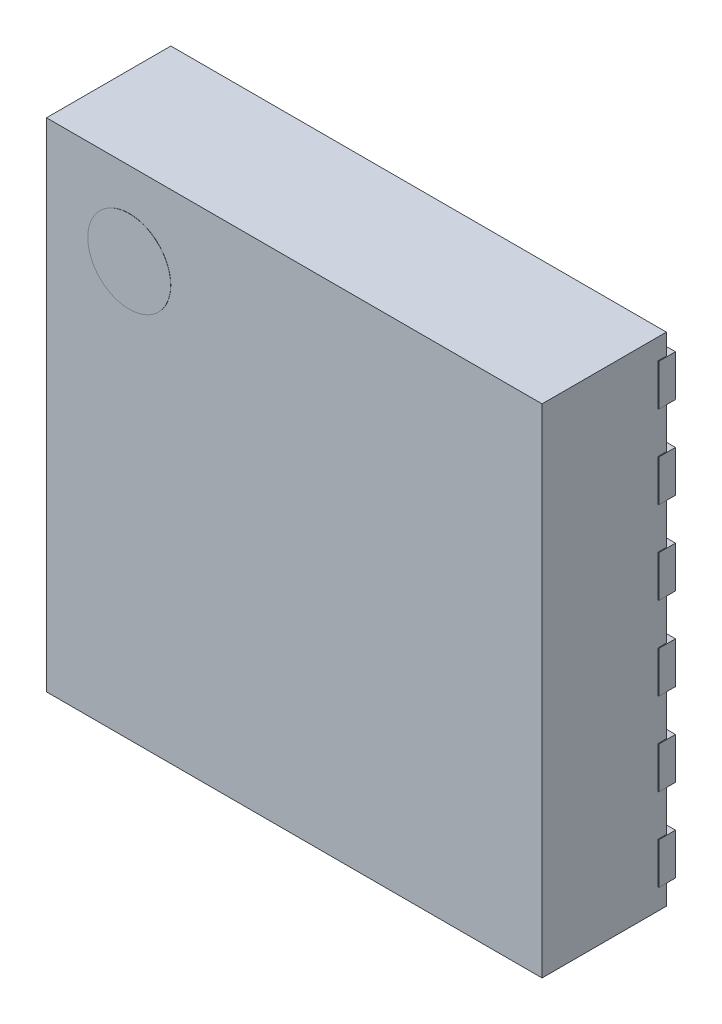
SolidWorks part; units mm, degrees
ref_plane "Plan de face" through (0, 0, 0) normal (0, 0, 1) x (1, 0, 0)
ref_plane "Plan de dessus" through (0, 0, 0) normal (0, 1, 0) x (1, 0, 0)
ref_plane "Plan de droite" through (0, 0, 0) normal (1, 0, 0) x (0, 0, -1)
sketch "Esquisse1" plane through (0, 0, 0) normal (0, 0, 1) x (1, 0, 0)
  line L1 (1.495, -1.5) -> (-1.495, -1.5)
  line L2 (1.495, -1.5) -> (1.495, 1.5)
  line L3 (1.495, 1.5) -> (-1.495, 1.5)
  line L4 (-1.495, -1.5) -> (-1.495, 1.5)
  line L5 (1.495, -1.5) -> (-1.495, 1.5) construction
  line L6 (1.495, 1.5) -> (-1.495, -1.5) construction
  point P0 (0, 0)
  dimension "D1" = 3
  dimension "D2" = 2.99
extrude "base" add sketch "Esquisse1" along normal blind 0.75 from offset 0.05
sketch "Esquisse3" plane through (0, 0, 0) normal (0, 0, 1) x (1, 0, 0)
  line L0 (-1.5, 1.375) -> (-1.205, 1.375)
  line L1 (-1.205, 1.125) -> (-1.5, 1.125)
  line L2 (-1.5, 1.125) -> (-1.5, 1.375)
  line L4 (-1.205, 0.625) -> (-1.5, 0.625)
  line L5 (-1.5, 0.625) -> (-1.5, 0.875)
  line L6 (-1.5, 0.875) -> (-1.205, 0.875)
  line L7 (-1.205, 0.125) -> (-1.5, 0.125)
  line L8 (-1.5, 0.125) -> (-1.5, 0.375)
  line L9 (-1.5, 0.375) -> (-1.205, 0.375)
  line L10 (-1.205, -0.375) -> (-1.5, -0.375)
  line L11 (-1.5, -0.375) -> (-1.5, -0.125)
  line L12 (-1.5, -0.125) -> (-1.205, -0.125)
  line L13 (-1.205, -0.875) -> (-1.5, -0.875)
  line L14 (-1.5, -0.875) -> (-1.5, -0.625)
  line L15 (-1.5, -0.625) -> (-1.205, -0.625)
  line L16 (-1.205, -1.375) -> (-1.5, -1.375)
  line L17 (-1.5, -1.375) -> (-1.5, -1.125)
  line L18 (-1.5, -1.125) -> (-1.205, -1.125)
  line L19 (-1.205, 1.125) -> (-1.205, 0.625) construction
  line L20 (0, 1.5) -> (0, -1.5) construction
  line L21 (1.495, 1.5) -> (-1.495, 1.5) construction
  line L22 (-1.495, -1.5) -> (1.495, -1.5) construction
  line L23 (1.5, 1.375) -> (1.205, 1.375)
  line L24 (1.5, 1.125) -> (1.5, 1.375)
  line L25 (1.205, 1.125) -> (1.5, 1.125)
  line L26 (1.5, -1.125) -> (1.205, -1.125)
  line L27 (1.5, -1.375) -> (1.5, -1.125)
  line L28 (1.205, -1.375) -> (1.5, -1.375)
  line L29 (1.5, -0.625) -> (1.205, -0.625)
  line L30 (1.5, -0.875) -> (1.5, -0.625)
  line L31 (1.205, -0.875) -> (1.5, -0.875)
  line L32 (1.5, -0.125) -> (1.205, -0.125)
  line L33 (1.5, -0.375) -> (1.5, -0.125)
  line L34 (1.205, -0.375) -> (1.5, -0.375)
  line L35 (1.5, 0.375) -> (1.205, 0.375)
  line L36 (1.5, 0.125) -> (1.5, 0.375)
  line L37 (1.205, 0.125) -> (1.5, 0.125)
  line L38 (1.5, 0.875) -> (1.205, 0.875)
  line L39 (1.5, 0.625) -> (1.5, 0.875)
  line L40 (1.205, 0.625) -> (1.5, 0.625)
  line L41 (-0.65, -1.25) -> (0.65, -1.25)
  line L42 (0.65, -1.25) -> (0.65, 1.25)
  line L43 (0.65, 1.25) -> (-0.35, 1.25)
  line L44 (-0.35, 1.25) -> (-0.65, 0.95)
  line L45 (-0.65, 0.95) -> (-0.65, -1.25)
  arc A0 (-1.205, 1.375) -> (-1.205, 1.125) centre (-1.205, 1.25) cw
  arc A1 (-1.205, 0.875) -> (-1.205, 0.625) centre (-1.205, 0.75) cw
  arc A2 (-1.205, 0.375) -> (-1.205, 0.125) centre (-1.205, 0.25) cw
  arc A3 (-1.205, -0.125) -> (-1.205, -0.375) centre (-1.205, -0.25) cw
  arc A4 (-1.205, -0.625) -> (-1.205, -0.875) centre (-1.205, -0.75) cw
  arc A5 (-1.205, -1.125) -> (-1.205, -1.375) centre (-1.205, -1.25) cw
  arc A6 (1.205, 1.375) -> (1.205, 1.125) centre (1.205, 1.25) ccw
  arc A7 (1.205, -1.125) -> (1.205, -1.375) centre (1.205, -1.25) ccw
  arc A8 (1.205, -0.625) -> (1.205, -0.875) centre (1.205, -0.75) ccw
  arc A9 (1.205, -0.125) -> (1.205, -0.375) centre (1.205, -0.25) ccw
  arc A10 (1.205, 0.375) -> (1.205, 0.125) centre (1.205, 0.25) ccw
  arc A11 (1.205, 0.875) -> (1.205, 0.625) centre (1.205, 0.75) ccw
  point P4 (-1.08, 1.25)
  point P75 (0, 0)
  point P76 (0, -1.25)
  point P77 (0.65, 0)
  dimension "D1" = 0.25
  dimension "D2" = 0.42
  dimension "D3" = 0.5
  dimension "D4" = 1.25
  dimension "D5" = 1.3
  dimension "D6" = 6
  dimension "D7" = 3
  dimension "D8" = 2.5
  dimension "D9" = 0.3
  dimension "D10" = 0.3
extrude "pads" add sketch "Esquisse3" along normal blind 0.1
sketch "Esquisse4" plane through (0, 0, 0.8) normal (0, 0, 1) x (1, 0, 0)
  line L0 (-1.495, 1.5) -> (-1.495, -1.5) construction
  line L1 (1.495, 1.5) -> (-1.495, 1.5) construction
  circle A0 centre (-0.995, 1) radius 0.25
  dimension "D1" = 0.5
  dimension "D3" = 0.5
  dimension "D2" = 0.5
extrude "mark" add sketch "Esquisse4" along normal blind 0.001
